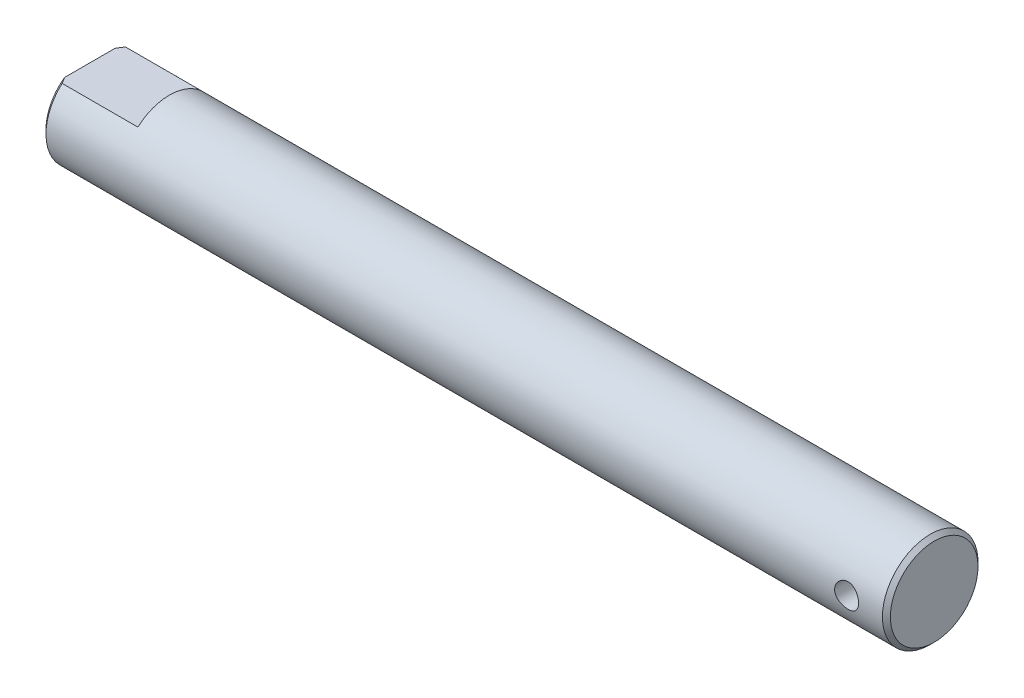
SolidWorks part; units mm, degrees
ref_plane "Front Plane" through (0, 0, 0) normal (0, 0, 1) x (1, 0, 0)
ref_plane "Top Plane" through (0, 0, 0) normal (0, 1, 0) x (1, 0, 0)
ref_plane "Right Plane" through (0, 0, 0) normal (1, 0, 0) x (0, 0, -1)
sketch "Sketch1" plane through (0, 0, 0) normal (1, 0, 0) x (0, 0, -1)
  circle A0 centre (0, 0) radius 6
  dimension "D1" = 12
extrude "Boss-Extrude1" add sketch "Sketch1" along normal blind 106
chamfer "Chamfer1" distance 0.5 angle 45 2 edges at (0, 0, -6) (106, 0, -6)
sketch "Sketch2" plane through (0, 0, 0) normal (-1, 0, 0) x (0, 0, 1)
  line L1 (-5.7626, 7.2098) -> (5.9684, 7.2098)
  line L2 (-5.7626, 7.2098) -> (-5.7626, 4.5)
  line L3 (-5.7626, 4.5) -> (5.9684, 4.5)
  line L4 (5.9684, 7.2098) -> (5.9684, 4.5)
  dimension "D1" = 4.5
extrude "Cut-Extrude1" cut sketch "Sketch2" against normal blind 10
sketch "Sketch3" plane through (0, 0, 0) normal (0, 0, 1) x (1, 0, 0)
  line L0 (106, -5.5) -> (106, 5.5) construction
  circle A0 centre (101, 0) radius 1.5
  dimension "D1" = 3
  dimension "D2" = 5
extrude "Cut-Extrude2" cut sketch "Sketch3" against normal through all both and the other way through all
